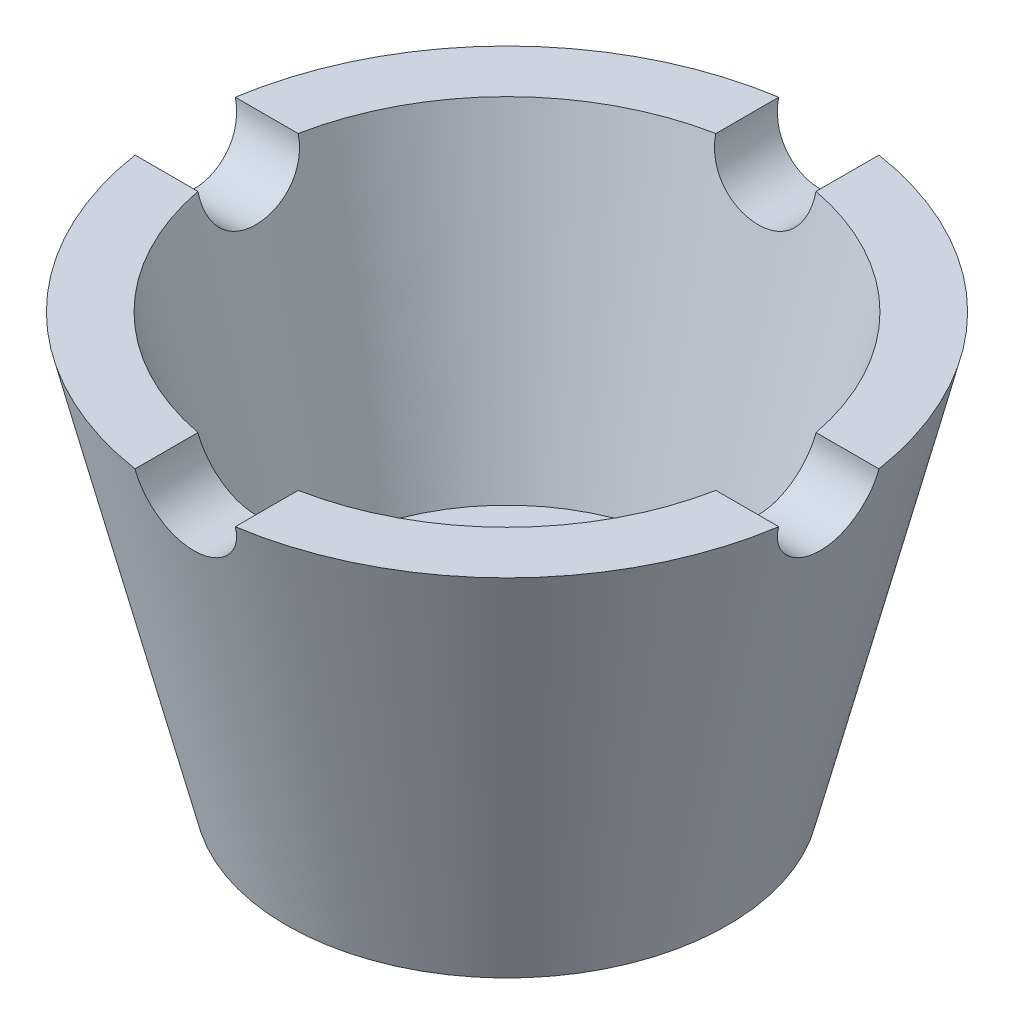
SolidWorks part; units mm, degrees
ref_plane "Front Plane" through (0, 0, 0) normal (0, 0, 1) x (1, 0, 0)
ref_plane "Top Plane" through (0, 0, 0) normal (0, 1, 0) x (1, 0, 0)
ref_plane "Right Plane" through (0, 0, 0) normal (1, 0, 0) x (0, 0, -1)
sketch "Sketch2" plane through (0, 0, 0) normal (0, 0, 1) x (1, 0, 0)
  line L1 (22, -42) -> (32.5, 0)
  line L2 (32.5, 0) -> (26.3153, 0)
  line L3 (0, 41.4385) -> (0, -84.7765) construction
  line L4 (11.25, -30) -> (18.8153, -30)
  line L5 (18.8153, -30) -> (26.3153, 0)
  line L7 (11.25, -30) -> (11.25, -42)
  line L8 (11.25, -42) -> (22, -42)
  dimension "D1" = 6
  dimension "D5" = 42
  dimension "D2" = 22
  dimension "D3" = 11.25
  dimension "D4" = 32.5
  dimension "D6" = 12
revolve "Revolve1" add sketch "Sketch2" angle 360 about L3
sketch "Sketch5" plane through (0, 0, 0) normal (0, 0, 1) x (1, 0, 0)
  circle A0 centre (0, 0) radius 5
  dimension "D1" = 10
extrude "Cut-Extrude2" cut sketch "Sketch5" against normal through all both and the other way through all
sketch "Sketch6" plane through (0, 0, 0) normal (1, 0, 0) x (0, 0, -1)
  circle A0 centre (0, 0) radius 5
  dimension "D1" = 10
extrude "Cut-Extrude3" cut sketch "Sketch6" against normal through all both and the other way through all
